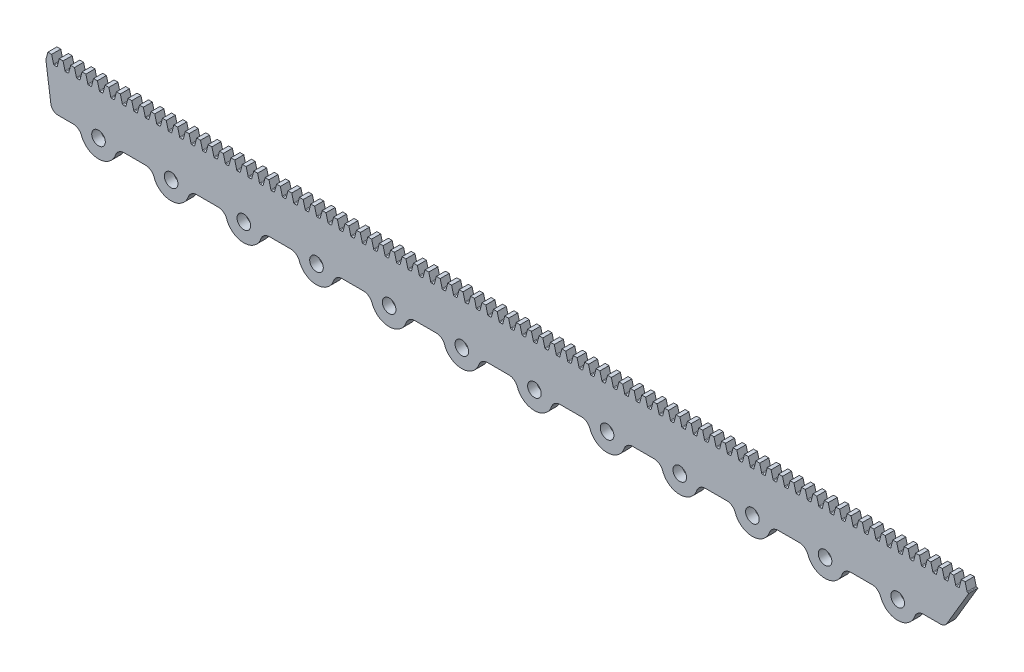
SolidWorks part; units mm, degrees
ref_plane "Front Plane" through (0, 0, 0) normal (0, 0, 1) x (1, 0, 0)
ref_plane "Top Plane" through (0, 0, 0) normal (0, 1, 0) x (1, 0, 0)
ref_plane "Right Plane" through (0, 0, 0) normal (1, 0, 0) x (0, 0, -1)
sketch "Sketch1" plane through (0, 0, 0) normal (0, 0, 1) x (1, 0, 0)
  line L0 (-103.4924, -0.9774) -> (-95.7557, 12.0777)
  line L4 (-379.696, 12.2681) -> (-380.3824, 14.9225)
  line L5 (-380.3824, 14.9225) -> (-381.7205, 14.9225)
  line L6 (-381.7205, 14.9225) -> (-382.4069, 12.2681)
  line L7 (-382.6528, 12.0777) -> (-383.4632, 12.0777)
  line L8 (-383.7092, 12.2681) -> (-384.3956, 14.9225)
  line L9 (-384.3956, 14.9225) -> (-385.7337, 14.9225)
  line L11 (-385.7337, 14.9225) -> (-386.4201, 12.2681)
  line L12 (-386.666, 12.0777) -> (-387.4764, 12.0777)
  line L13 (-387.7224, 12.2681) -> (-388.4088, 14.9225)
  line L14 (-388.4088, 14.9225) -> (-389.7469, 14.9225)
  line L15 (-389.7469, 14.9225) -> (-390.4333, 12.2681)
  line L16 (-390.6792, 12.0777) -> (-391.4896, 12.0777)
  line L17 (-391.7356, 12.2681) -> (-392.422, 14.9225)
  line L18 (-392.422, 14.9225) -> (-393.7601, 14.9225)
  line L19 (-393.7601, 14.9225) -> (-394.4465, 12.2681)
  line L20 (-394.6924, 12.0777) -> (-395.5028, 12.0777)
  line L21 (-395.7488, 12.2681) -> (-396.4352, 14.9225)
  line L22 (-396.4352, 14.9225) -> (-397.7733, 14.9225)
  line L23 (-397.7733, 14.9225) -> (-398.4597, 12.2681)
  line L24 (-398.7056, 12.0777) -> (-399.516, 12.0777)
  line L25 (-399.762, 12.2681) -> (-400.4484, 14.9225)
  line L26 (-400.4484, 14.9225) -> (-401.7865, 14.9225)
  line L27 (-401.7865, 14.9225) -> (-402.4729, 12.2681)
  line L28 (-402.7188, 12.0777) -> (-403.5292, 12.0777)
  line L29 (-403.7752, 12.2681) -> (-404.4616, 14.9225)
  line L30 (-404.4616, 14.9225) -> (-405.7997, 14.9225)
  line L31 (-405.7997, 14.9225) -> (-406.4861, 12.2681)
  line L32 (-406.732, 12.0777) -> (-407.5103, 12.0777)
  line L34 (-407.765, 12.2681) -> (-408.4515, 14.9225)
  line L35 (-408.4515, 14.9225) -> (-409.7895, 14.9225)
  line L36 (-409.7895, 14.9225) -> (-410.4759, 12.2681)
  line L37 (-411.5089, 12.0777) -> (-410.7219, 12.0777)
  line L38 (-415.7446, 12.2681) -> (-416.4311, 14.9225)
  line L39 (-416.4311, 14.9225) -> (-417.7691, 14.9225)
  line L40 (-417.7691, 14.9225) -> (-418.3293, 12.7565)
  line L41 (-391.0698, -2.2225) -> (-383.6303, -2.2225)
  line L42 (-411.7548, 12.2681) -> (-412.4413, 14.9225)
  line L43 (-412.4413, 14.9225) -> (-413.7793, 14.9225)
  line L44 (-413.7793, 14.9225) -> (-414.4658, 12.2681)
  line L48 (-414.1934, -2.4033) -> (-408.9633, -2.4033)
  line L49 (-418.3857, 11.7685) -> (-416.7089, -0.2153)
  line L50 (-415.4987, 12.0777) -> (-414.7117, 12.0777)
  line L1890 (-365.6698, -2.2225) -> (-358.2303, -2.2225)
  line L1891 (-340.2698, -2.2225) -> (-332.8303, -2.2225)
  line L1892 (-314.8698, -2.2225) -> (-307.4303, -2.2225)
  line L1893 (-289.4698, -2.2225) -> (-282.0303, -2.2225)
  line L1894 (-264.0698, -2.2225) -> (-256.6303, -2.2225)
  line L1895 (-238.6698, -2.2225) -> (-231.2303, -2.2225)
  line L1896 (-213.2698, -2.2225) -> (-205.8303, -2.2225)
  line L1897 (-187.8698, -2.2225) -> (-180.4303, -2.2225)
  line L1898 (-162.4698, -2.2225) -> (-155.0303, -2.2225)
  line L1899 (-137.0698, -2.2225) -> (-129.6303, -2.2225)
  line L1900 (-111.6698, -2.2225) -> (-105.6776, -2.2225)
  line L2472 (-95.7557, 12.0777) -> (-96.1493, 12.0777)
  line L2473 (-96.3952, 12.2681) -> (-97.0816, 14.9225)
  line L2474 (-97.0816, 14.9225) -> (-98.4197, 14.9225)
  line L2475 (-98.4197, 14.9225) -> (-99.1061, 12.2681)
  line L2476 (-99.352, 12.0777) -> (-100.1391, 12.0777)
  line L2477 (-100.385, 12.2681) -> (-101.0715, 14.9225)
  line L2478 (-101.0715, 14.9225) -> (-102.4095, 14.9225)
  line L2479 (-102.4095, 14.9225) -> (-103.096, 12.2681)
  line L2480 (-103.3419, 12.0777) -> (-104.1289, 12.0777)
  line L2481 (-104.3748, 12.2681) -> (-105.0613, 14.9225)
  line L2482 (-105.0613, 14.9225) -> (-106.3993, 14.9225)
  line L2483 (-106.3993, 14.9225) -> (-107.0858, 12.2681)
  line L2484 (-107.3317, 12.0777) -> (-108.1187, 12.0777)
  line L2485 (-108.3646, 12.2681) -> (-109.0511, 14.9225)
  line L2486 (-109.0511, 14.9225) -> (-110.3891, 14.9225)
  line L2487 (-110.3891, 14.9225) -> (-111.0756, 12.2681)
  line L2488 (-111.3215, 12.0777) -> (-112.1086, 12.0777)
  line L2489 (-112.3545, 12.2681) -> (-113.0409, 14.9225)
  line L2490 (-113.0409, 14.9225) -> (-114.379, 14.9225)
  line L2491 (-114.379, 14.9225) -> (-115.0654, 12.2681)
  line L2492 (-115.3113, 12.0777) -> (-116.0984, 12.0777)
  line L2493 (-116.3443, 12.2681) -> (-117.0308, 14.9225)
  line L2494 (-117.0308, 14.9225) -> (-118.3688, 14.9225)
  line L2495 (-118.3688, 14.9225) -> (-119.0553, 12.2681)
  line L2496 (-119.3012, 12.0777) -> (-120.0882, 12.0777)
  line L2497 (-120.3341, 12.2681) -> (-121.0206, 14.9225)
  line L2498 (-121.0206, 14.9225) -> (-122.3586, 14.9225)
  line L2499 (-122.3586, 14.9225) -> (-123.0451, 12.2681)
  line L2500 (-123.291, 12.0777) -> (-124.078, 12.0777)
  line L2501 (-124.3239, 12.2681) -> (-125.0104, 14.9225)
  line L2502 (-125.0104, 14.9225) -> (-126.3484, 14.9225)
  line L2503 (-126.3484, 14.9225) -> (-127.0349, 12.2681)
  line L2504 (-127.2808, 12.0777) -> (-128.0678, 12.0777)
  line L2505 (-128.3138, 12.2681) -> (-129.0002, 14.9225)
  line L2506 (-129.0002, 14.9225) -> (-130.3382, 14.9225)
  line L2507 (-130.3382, 14.9225) -> (-131.0247, 12.2681)
  line L2508 (-131.2706, 12.0777) -> (-132.0577, 12.0777)
  line L2509 (-132.3036, 12.2681) -> (-132.99, 14.9225)
  line L2510 (-132.99, 14.9225) -> (-134.3281, 14.9225)
  line L2511 (-134.3281, 14.9225) -> (-135.0145, 12.2681)
  line L2512 (-135.2605, 12.0777) -> (-136.0475, 12.0777)
  line L2513 (-136.2934, 12.2681) -> (-136.9799, 14.9225)
  line L2514 (-136.9799, 14.9225) -> (-138.3179, 14.9225)
  line L2515 (-138.3179, 14.9225) -> (-139.0044, 12.2681)
  line L2516 (-139.2503, 12.0777) -> (-140.0373, 12.0777)
  line L2517 (-140.2832, 12.2681) -> (-140.9697, 14.9225)
  line L2518 (-140.9697, 14.9225) -> (-142.3077, 14.9225)
  line L2519 (-142.3077, 14.9225) -> (-142.9942, 12.2681)
  line L2520 (-143.2401, 12.0777) -> (-144.0271, 12.0777)
  line L2521 (-144.273, 12.2681) -> (-144.9595, 14.9225)
  line L2522 (-144.9595, 14.9225) -> (-146.2975, 14.9225)
  line L2523 (-146.2975, 14.9225) -> (-146.984, 12.2681)
  line L2524 (-147.2299, 12.0777) -> (-148.017, 12.0777)
  line L2525 (-148.2629, 12.2681) -> (-148.9493, 14.9225)
  line L2526 (-148.9493, 14.9225) -> (-150.2874, 14.9225)
  line L2527 (-150.2874, 14.9225) -> (-150.9738, 12.2681)
  line L2528 (-151.2197, 12.0777) -> (-152.0068, 12.0777)
  line L2529 (-152.2527, 12.2681) -> (-152.9392, 14.9225)
  line L2530 (-152.9392, 14.9225) -> (-154.2772, 14.9225)
  line L2531 (-154.2772, 14.9225) -> (-154.9637, 12.2681)
  line L2532 (-155.2096, 12.0777) -> (-155.9966, 12.0777)
  line L2533 (-156.2425, 12.2681) -> (-156.929, 14.9225)
  line L2534 (-156.929, 14.9225) -> (-158.267, 14.9225)
  line L2535 (-158.267, 14.9225) -> (-158.9535, 12.2681)
  line L2536 (-159.1994, 12.0777) -> (-159.9864, 12.0777)
  line L2537 (-160.2323, 12.2681) -> (-160.9188, 14.9225)
  line L2538 (-160.9188, 14.9225) -> (-162.2568, 14.9225)
  line L2539 (-162.2568, 14.9225) -> (-162.9433, 12.2681)
  line L2540 (-163.1892, 12.0777) -> (-163.9762, 12.0777)
  line L2541 (-164.2222, 12.2681) -> (-164.9086, 14.9225)
  line L2542 (-164.9086, 14.9225) -> (-166.2467, 14.9225)
  line L2543 (-166.2467, 14.9225) -> (-166.9331, 12.2681)
  line L2544 (-167.179, 12.0777) -> (-167.9661, 12.0777)
  line L2545 (-168.212, 12.2681) -> (-168.8985, 14.9225)
  line L2546 (-168.8985, 14.9225) -> (-170.2365, 14.9225)
  line L2547 (-170.2365, 14.9225) -> (-170.9229, 12.2681)
  line L2548 (-171.1689, 12.0777) -> (-171.9559, 12.0777)
  line L2549 (-172.2018, 12.2681) -> (-172.8883, 14.9225)
  line L2550 (-172.8883, 14.9225) -> (-174.2263, 14.9225)
  line L2551 (-174.2263, 14.9225) -> (-174.9128, 12.2681)
  line L2552 (-175.1587, 12.0777) -> (-175.9457, 12.0777)
  line L2553 (-176.1916, 12.2681) -> (-176.8781, 14.9225)
  line L2554 (-176.8781, 14.9225) -> (-178.2161, 14.9225)
  line L2555 (-178.2161, 14.9225) -> (-178.9026, 12.2681)
  line L2556 (-179.1485, 12.0777) -> (-179.9355, 12.0777)
  line L2557 (-180.1814, 12.2681) -> (-180.8679, 14.9225)
  line L2558 (-180.8679, 14.9225) -> (-182.2059, 14.9225)
  line L2559 (-182.2059, 14.9225) -> (-182.8924, 12.2681)
  line L2560 (-183.1383, 12.0777) -> (-183.9254, 12.0777)
  line L2561 (-184.1713, 12.2681) -> (-184.8577, 14.9225)
  line L2562 (-184.8577, 14.9225) -> (-186.1958, 14.9225)
  line L2563 (-186.1958, 14.9225) -> (-186.8822, 12.2681)
  line L2564 (-187.1281, 12.0777) -> (-187.9152, 12.0777)
  line L2565 (-188.1611, 12.2681) -> (-188.8476, 14.9225)
  line L2566 (-188.8476, 14.9225) -> (-190.1856, 14.9225)
  line L2567 (-190.1856, 14.9225) -> (-190.8721, 12.2681)
  line L2568 (-191.118, 12.0777) -> (-191.905, 12.0777)
  line L2569 (-192.1509, 12.2681) -> (-192.8374, 14.9225)
  line L2570 (-192.8374, 14.9225) -> (-194.1754, 14.9225)
  line L2571 (-194.1754, 14.9225) -> (-194.8619, 12.2681)
  line L2572 (-195.1078, 12.0777) -> (-195.8948, 12.0777)
  line L2573 (-196.1407, 12.2681) -> (-196.8272, 14.9225)
  line L2574 (-196.8272, 14.9225) -> (-198.1652, 14.9225)
  line L2575 (-198.1652, 14.9225) -> (-198.8517, 12.2681)
  line L2576 (-199.0976, 12.0777) -> (-199.8847, 12.0777)
  line L2577 (-200.1306, 12.2681) -> (-200.817, 14.9225)
  line L2578 (-200.817, 14.9225) -> (-202.1551, 14.9225)
  line L2579 (-202.1551, 14.9225) -> (-202.8415, 12.2681)
  line L2580 (-203.0874, 12.0777) -> (-203.8745, 12.0777)
  line L2581 (-204.1204, 12.2681) -> (-204.8069, 14.9225)
  line L2582 (-204.8069, 14.9225) -> (-206.1449, 14.9225)
  line L2583 (-206.1449, 14.9225) -> (-206.8314, 12.2681)
  line L2584 (-207.0773, 12.0777) -> (-207.8643, 12.0777)
  line L2585 (-208.1102, 12.2681) -> (-208.7967, 14.9225)
  line L2586 (-208.7967, 14.9225) -> (-210.1347, 14.9225)
  line L2587 (-210.1347, 14.9225) -> (-210.8212, 12.2681)
  line L2588 (-211.0671, 12.0777) -> (-211.8541, 12.0777)
  line L2589 (-212.1, 12.2681) -> (-212.7865, 14.9225)
  line L2590 (-212.7865, 14.9225) -> (-214.1245, 14.9225)
  line L2591 (-214.1245, 14.9225) -> (-214.811, 12.2681)
  line L2592 (-215.0569, 12.0777) -> (-215.8439, 12.0777)
  line L2593 (-216.0899, 12.2681) -> (-216.7763, 14.9225)
  line L2594 (-216.7763, 14.9225) -> (-218.1143, 14.9225)
  line L2595 (-218.1143, 14.9225) -> (-218.8008, 12.2681)
  line L2596 (-219.0467, 12.0777) -> (-219.8338, 12.0777)
  line L2597 (-220.0797, 12.2681) -> (-220.7661, 14.9225)
  line L2598 (-220.7661, 14.9225) -> (-222.1042, 14.9225)
  line L2599 (-222.1042, 14.9225) -> (-222.7906, 12.2681)
  line L2600 (-223.0366, 12.0777) -> (-223.8236, 12.0777)
  line L2601 (-224.0695, 12.2681) -> (-224.756, 14.9225)
  line L2602 (-224.756, 14.9225) -> (-226.094, 14.9225)
  line L2603 (-226.094, 14.9225) -> (-226.7805, 12.2681)
  line L2604 (-227.0264, 12.0777) -> (-227.8134, 12.0777)
  line L2605 (-228.0593, 12.2681) -> (-228.7458, 14.9225)
  line L2606 (-228.7458, 14.9225) -> (-230.0838, 14.9225)
  line L2607 (-230.0838, 14.9225) -> (-230.7703, 12.2681)
  line L2608 (-231.0162, 12.0777) -> (-231.8032, 12.0777)
  line L2609 (-232.0491, 12.2681) -> (-232.7356, 14.9225)
  line L2610 (-232.7356, 14.9225) -> (-234.0736, 14.9225)
  line L2611 (-234.0736, 14.9225) -> (-234.7601, 12.2681)
  line L2612 (-235.006, 12.0777) -> (-235.7931, 12.0777)
  line L2613 (-236.039, 12.2681) -> (-236.7254, 14.9225)
  line L2614 (-236.7254, 14.9225) -> (-238.0635, 14.9225)
  line L2615 (-238.0635, 14.9225) -> (-238.7499, 12.2681)
  line L2616 (-238.9958, 12.0777) -> (-239.7829, 12.0777)
  line L2617 (-240.0288, 12.2681) -> (-240.7153, 14.9225)
  line L2618 (-240.7153, 14.9225) -> (-242.0533, 14.9225)
  line L2619 (-242.0533, 14.9225) -> (-242.7398, 12.2681)
  line L2620 (-242.9857, 12.0777) -> (-243.7727, 12.0777)
  line L2621 (-244.0186, 12.2681) -> (-244.7051, 14.9225)
  line L2622 (-244.7051, 14.9225) -> (-246.0431, 14.9225)
  line L2623 (-246.0431, 14.9225) -> (-246.7296, 12.2681)
  line L2624 (-246.9755, 12.0777) -> (-247.7625, 12.0777)
  line L2625 (-248.0084, 12.2681) -> (-248.6949, 14.9225)
  line L2626 (-248.6949, 14.9225) -> (-250.0329, 14.9225)
  line L2627 (-250.0329, 14.9225) -> (-250.7194, 12.2681)
  line L2628 (-250.9653, 12.0777) -> (-251.7523, 12.0777)
  line L2629 (-251.9983, 12.2681) -> (-252.6847, 14.9225)
  line L2630 (-252.6847, 14.9225) -> (-254.0228, 14.9225)
  line L2631 (-254.0228, 14.9225) -> (-254.7092, 12.2681)
  line L2632 (-254.9551, 12.0777) -> (-255.7422, 12.0777)
  line L2633 (-255.9881, 12.2681) -> (-256.6746, 14.9225)
  line L2634 (-256.6746, 14.9225) -> (-258.0126, 14.9225)
  line L2635 (-258.0126, 14.9225) -> (-258.699, 12.2681)
  line L2636 (-258.945, 12.0777) -> (-259.732, 12.0777)
  line L2637 (-259.9779, 12.2681) -> (-260.6644, 14.9225)
  line L2638 (-260.6644, 14.9225) -> (-262.0024, 14.9225)
  line L2639 (-262.0024, 14.9225) -> (-262.6889, 12.2681)
  line L2640 (-262.9348, 12.0777) -> (-263.7218, 12.0777)
  line L2641 (-263.9677, 12.2681) -> (-264.6542, 14.9225)
  line L2642 (-264.6542, 14.9225) -> (-265.9922, 14.9225)
  line L2643 (-265.9922, 14.9225) -> (-266.6787, 12.2681)
  line L2644 (-266.9246, 12.0777) -> (-267.7116, 12.0777)
  line L2645 (-267.9575, 12.2681) -> (-268.644, 14.9225)
  line L2646 (-268.644, 14.9225) -> (-269.982, 14.9225)
  line L2647 (-269.982, 14.9225) -> (-270.6685, 12.2681)
  line L2648 (-270.9144, 12.0777) -> (-271.7015, 12.0777)
  line L2649 (-271.9474, 12.2681) -> (-272.6338, 14.9225)
  line L2650 (-272.6338, 14.9225) -> (-273.9719, 14.9225)
  line L2651 (-273.9719, 14.9225) -> (-274.6583, 12.2681)
  line L2652 (-274.9042, 12.0777) -> (-275.6913, 12.0777)
  line L2653 (-275.9372, 12.2681) -> (-276.6237, 14.9225)
  line L2654 (-276.6237, 14.9225) -> (-277.9617, 14.9225)
  line L2655 (-277.9617, 14.9225) -> (-278.6482, 12.2681)
  line L2656 (-278.8941, 12.0777) -> (-279.6811, 12.0777)
  line L2657 (-279.927, 12.2681) -> (-280.6135, 14.9225)
  line L2658 (-280.6135, 14.9225) -> (-281.9515, 14.9225)
  line L2659 (-281.9515, 14.9225) -> (-282.638, 12.2681)
  line L2660 (-282.8839, 12.0777) -> (-283.6709, 12.0777)
  line L2661 (-283.9168, 12.2681) -> (-284.6033, 14.9225)
  line L2662 (-284.6033, 14.9225) -> (-285.9413, 14.9225)
  line L2663 (-285.9413, 14.9225) -> (-286.6278, 12.2681)
  line L2664 (-286.8737, 12.0777) -> (-287.6607, 12.0777)
  line L2665 (-287.9067, 12.2681) -> (-288.5931, 14.9225)
  line L2666 (-288.5931, 14.9225) -> (-289.9312, 14.9225)
  line L2667 (-289.9312, 14.9225) -> (-290.6176, 12.2681)
  line L2668 (-290.8635, 12.0777) -> (-291.6506, 12.0777)
  line L2669 (-291.8965, 12.2681) -> (-292.583, 14.9225)
  line L2670 (-292.583, 14.9225) -> (-293.921, 14.9225)
  line L2671 (-293.921, 14.9225) -> (-294.6075, 12.2681)
  line L2672 (-294.8534, 12.0777) -> (-295.6404, 12.0777)
  line L2673 (-295.8863, 12.2681) -> (-296.5728, 14.9225)
  line L2674 (-296.5728, 14.9225) -> (-297.9108, 14.9225)
  line L2675 (-297.9108, 14.9225) -> (-298.5973, 12.2681)
  line L2676 (-298.8432, 12.0777) -> (-299.6302, 12.0777)
  line L2677 (-299.8761, 12.2681) -> (-300.5626, 14.9225)
  line L2678 (-300.5626, 14.9225) -> (-301.9006, 14.9225)
  line L2679 (-301.9006, 14.9225) -> (-302.5871, 12.2681)
  line L2680 (-302.833, 12.0777) -> (-303.62, 12.0777)
  line L2681 (-303.8659, 12.2681) -> (-304.5524, 14.9225)
  line L2682 (-304.5524, 14.9225) -> (-305.8904, 14.9225)
  line L2683 (-305.8904, 14.9225) -> (-306.5769, 12.2681)
  line L2684 (-306.8228, 12.0777) -> (-307.6099, 12.0777)
  line L2685 (-307.8558, 12.2681) -> (-308.5422, 14.9225)
  line L2686 (-308.5422, 14.9225) -> (-309.8803, 14.9225)
  line L2687 (-309.8803, 14.9225) -> (-310.5667, 12.2681)
  line L2688 (-310.8127, 12.0777) -> (-311.5997, 12.0777)
  line L2689 (-311.8456, 12.2681) -> (-312.5321, 14.9225)
  line L2690 (-312.5321, 14.9225) -> (-313.8701, 14.9225)
  line L2691 (-313.8701, 14.9225) -> (-314.5566, 12.2681)
  line L2692 (-314.8025, 12.0777) -> (-315.5895, 12.0777)
  line L2693 (-315.8354, 12.2681) -> (-316.5219, 14.9225)
  line L2694 (-316.5219, 14.9225) -> (-317.8599, 14.9225)
  line L2695 (-317.8599, 14.9225) -> (-318.5464, 12.2681)
  line L2696 (-318.7923, 12.0777) -> (-319.5793, 12.0777)
  line L2697 (-319.8252, 12.2681) -> (-320.5117, 14.9225)
  line L2698 (-320.5117, 14.9225) -> (-321.8497, 14.9225)
  line L2699 (-321.8497, 14.9225) -> (-322.5362, 12.2681)
  line L2700 (-322.7821, 12.0777) -> (-323.5692, 12.0777)
  line L2701 (-323.8151, 12.2681) -> (-324.5015, 14.9225)
  line L2702 (-324.5015, 14.9225) -> (-325.8396, 14.9225)
  line L2703 (-325.8396, 14.9225) -> (-326.526, 12.2681)
  line L2704 (-326.7719, 12.0777) -> (-327.559, 12.0777)
  line L2705 (-327.8049, 12.2681) -> (-328.4914, 14.9225)
  line L2706 (-328.4914, 14.9225) -> (-329.8294, 14.9225)
  line L2707 (-329.8294, 14.9225) -> (-330.5159, 12.2681)
  line L2708 (-330.7618, 12.0777) -> (-331.5488, 12.0777)
  line L2709 (-331.7947, 12.2681) -> (-332.4812, 14.9225)
  line L2710 (-332.4812, 14.9225) -> (-333.8192, 14.9225)
  line L2711 (-333.8192, 14.9225) -> (-334.5057, 12.2681)
  line L2712 (-334.7516, 12.0777) -> (-335.5386, 12.0777)
  line L2713 (-335.7845, 12.2681) -> (-336.471, 14.9225)
  line L2714 (-336.471, 14.9225) -> (-337.809, 14.9225)
  line L2715 (-337.809, 14.9225) -> (-338.4955, 12.2681)
  line L2716 (-338.7414, 12.0777) -> (-339.5284, 12.0777)
  line L2717 (-339.7744, 12.2681) -> (-340.4608, 14.9225)
  line L2718 (-340.4608, 14.9225) -> (-341.7988, 14.9225)
  line L2719 (-341.7988, 14.9225) -> (-342.4853, 12.2681)
  line L2720 (-342.7312, 12.0777) -> (-343.5183, 12.0777)
  line L2721 (-343.7642, 12.2681) -> (-344.4506, 14.9225)
  line L2722 (-344.4506, 14.9225) -> (-345.7887, 14.9225)
  line L2723 (-345.7887, 14.9225) -> (-346.4751, 12.2681)
  line L2724 (-346.7211, 12.0777) -> (-347.5081, 12.0777)
  line L2725 (-347.754, 12.2681) -> (-348.4405, 14.9225)
  line L2726 (-348.4405, 14.9225) -> (-349.7785, 14.9225)
  line L2727 (-349.7785, 14.9225) -> (-350.465, 12.2681)
  line L2728 (-350.7109, 12.0777) -> (-351.4979, 12.0777)
  line L2729 (-351.7438, 12.2681) -> (-352.4303, 14.9225)
  line L2730 (-352.4303, 14.9225) -> (-353.7683, 14.9225)
  line L2731 (-353.7683, 14.9225) -> (-354.4548, 12.2681)
  line L2732 (-354.7007, 12.0777) -> (-355.4877, 12.0777)
  line L2733 (-355.7336, 12.2681) -> (-356.4201, 14.9225)
  line L2734 (-356.4201, 14.9225) -> (-357.7581, 14.9225)
  line L2735 (-357.7581, 14.9225) -> (-358.4446, 12.2681)
  line L2736 (-358.6905, 12.0777) -> (-359.4776, 12.0777)
  line L2737 (-359.7235, 12.2681) -> (-360.4099, 14.9225)
  line L2738 (-360.4099, 14.9225) -> (-361.748, 14.9225)
  line L2739 (-361.748, 14.9225) -> (-362.4344, 12.2681)
  line L2740 (-362.6803, 12.0777) -> (-363.4674, 12.0777)
  line L2741 (-363.7133, 12.2681) -> (-364.3998, 14.9225)
  line L2742 (-364.3998, 14.9225) -> (-365.7378, 14.9225)
  line L2743 (-365.7378, 14.9225) -> (-366.4243, 12.2681)
  line L2744 (-366.6702, 12.0777) -> (-367.4572, 12.0777)
  line L2745 (-367.7031, 12.2681) -> (-368.3896, 14.9225)
  line L2746 (-368.3896, 14.9225) -> (-369.7276, 14.9225)
  line L2747 (-369.7276, 14.9225) -> (-370.4141, 12.2681)
  line L2748 (-370.66, 12.0777) -> (-371.447, 12.0777)
  line L2749 (-371.6929, 12.2681) -> (-372.3794, 14.9225)
  line L2750 (-372.3794, 14.9225) -> (-373.7174, 14.9225)
  line L2751 (-373.7174, 14.9225) -> (-374.4039, 12.2681)
  line L2752 (-374.6498, 12.0777) -> (-375.4368, 12.0777)
  line L2753 (-375.6828, 12.2681) -> (-376.3692, 14.9225)
  line L2754 (-376.3692, 14.9225) -> (-377.7073, 14.9225)
  line L2755 (-377.7073, 14.9225) -> (-378.3937, 12.2681)
  line L2756 (-378.6396, 12.0777) -> (-379.45, 12.0777)
  arc A0 (-105.6776, -2.2225) -> (-103.4924, -0.9774) centre (-105.6776, 0.3175) ccw
  circle A5 centre (-374.65, -2.2225) radius 2.3813
  circle A6 centre (-349.25, -2.2225) radius 2.3813
  circle A7 centre (-323.85, -2.2225) radius 2.3813
  circle A8 centre (-298.45, -2.2225) radius 2.3813
  circle A9 centre (-273.05, -2.2225) radius 2.3813
  circle A10 centre (-247.65, -2.2225) radius 2.3813
  circle A11 centre (-222.25, -2.2225) radius 2.3813
  circle A12 centre (-196.85, -2.2225) radius 2.3813
  circle A13 centre (-171.45, -2.2225) radius 2.3813
  circle A14 centre (-146.05, -2.2225) radius 2.3813
  circle A15 centre (-120.65, -2.2225) radius 2.3813
  arc A17 (-382.6528, 12.0777) -> (-382.4069, 12.2681) centre (-382.6528, 12.3317) ccw
  arc A18 (-379.696, 12.2681) -> (-379.45, 12.0777) centre (-379.45, 12.3317) ccw
  arc A19 (-405.9698, -4.52) -> (-394.0632, -4.3392) centre (-400.05, -2.2225) ccw
  arc A20 (-386.666, 12.0777) -> (-386.4201, 12.2681) centre (-386.666, 12.3317) ccw
  arc A21 (-383.7092, 12.2681) -> (-383.4632, 12.0777) centre (-383.4632, 12.3317) ccw
  arc A22 (-390.6792, 12.0777) -> (-390.4333, 12.2681) centre (-390.6792, 12.3317) ccw
  arc A23 (-387.7224, 12.2681) -> (-387.4764, 12.0777) centre (-387.4764, 12.3317) ccw
  arc A24 (-394.6924, 12.0777) -> (-394.4465, 12.2681) centre (-394.6924, 12.3317) ccw
  arc A25 (-391.7356, 12.2681) -> (-391.4896, 12.0777) centre (-391.4896, 12.3317) ccw
  arc A26 (-398.7056, 12.0777) -> (-398.4597, 12.2681) centre (-398.7056, 12.3317) ccw
  circle A27 centre (-400.05, -2.2225) radius 2.3813
  arc A28 (-395.7488, 12.2681) -> (-395.5028, 12.0777) centre (-395.5028, 12.3317) ccw
  arc A29 (-402.7188, 12.0777) -> (-402.4729, 12.2681) centre (-402.7188, 12.3317) ccw
  arc A31 (-399.762, 12.2681) -> (-399.516, 12.0777) centre (-399.516, 12.3317) ccw
  arc A33 (-406.732, 12.0777) -> (-406.4861, 12.2681) centre (-406.732, 12.3317) ccw
  arc A34 (-403.7752, 12.2681) -> (-403.5292, 12.0777) centre (-403.5292, 12.3317) ccw
  arc A35 (-410.7219, 12.0777) -> (-410.4759, 12.2681) centre (-410.7219, 12.3317) ccw
  arc A36 (-407.765, 12.2681) -> (-407.5103, 12.0777) centre (-407.5189, 12.3317) ccw
  arc A37 (-394.0632, -4.3392) -> (-391.0698, -2.2225) centre (-391.0698, -5.3975) cw
  arc A38 (-415.7446, 12.2681) -> (-415.4987, 12.0777) centre (-415.4987, 12.3317) ccw
  arc A39 (-414.7117, 12.0777) -> (-414.4658, 12.2681) centre (-414.7117, 12.3317) ccw
  arc A40 (-411.7548, 12.2681) -> (-411.5089, 12.0777) centre (-411.5089, 12.3317) ccw
  arc A41 (-408.9633, -2.4033) -> (-405.9698, -4.52) centre (-408.9633, -5.5783) cw
  arc A43 (-383.6303, -2.2225) -> (-380.6369, -4.3392) centre (-383.6303, -5.3975) cw
  arc A44 (-416.7089, -0.2153) -> (-414.1934, -2.4033) centre (-414.1934, 0.1367) ccw
  arc A45 (-418.3293, 12.7565) -> (-418.3857, 11.7685) centre (-415.8702, 12.1205) ccw
  arc A1126 (-380.6369, -4.3392) -> (-368.6632, -4.3392) centre (-374.65, -2.2225) ccw
  arc A1127 (-365.6698, -2.2225) -> (-368.6632, -4.3392) centre (-365.6698, -5.3975) ccw
  arc A1128 (-355.2369, -4.3392) -> (-358.2303, -2.2225) centre (-358.2303, -5.3975) ccw
  arc A1129 (-355.2369, -4.3392) -> (-343.2632, -4.3392) centre (-349.25, -2.2225) ccw
  arc A1130 (-340.2698, -2.2225) -> (-343.2632, -4.3392) centre (-340.2698, -5.3975) ccw
  arc A1131 (-329.8369, -4.3392) -> (-332.8303, -2.2225) centre (-332.8303, -5.3975) ccw
  arc A1132 (-329.8369, -4.3392) -> (-317.8632, -4.3392) centre (-323.85, -2.2225) ccw
  arc A1133 (-314.8698, -2.2225) -> (-317.8632, -4.3392) centre (-314.8698, -5.3975) ccw
  arc A1134 (-304.4369, -4.3392) -> (-307.4303, -2.2225) centre (-307.4303, -5.3975) ccw
  arc A1135 (-304.4369, -4.3392) -> (-292.4632, -4.3392) centre (-298.45, -2.2225) ccw
  arc A1136 (-289.4698, -2.2225) -> (-292.4632, -4.3392) centre (-289.4698, -5.3975) ccw
  arc A1137 (-279.0369, -4.3392) -> (-282.0303, -2.2225) centre (-282.0303, -5.3975) ccw
  arc A1138 (-279.0369, -4.3392) -> (-267.0632, -4.3392) centre (-273.05, -2.2225) ccw
  arc A1139 (-264.0698, -2.2225) -> (-267.0632, -4.3392) centre (-264.0698, -5.3975) ccw
  arc A1140 (-253.6369, -4.3392) -> (-256.6303, -2.2225) centre (-256.6303, -5.3975) ccw
  arc A1141 (-253.6369, -4.3392) -> (-241.6632, -4.3392) centre (-247.65, -2.2225) ccw
  arc A1142 (-238.6698, -2.2225) -> (-241.6632, -4.3392) centre (-238.6698, -5.3975) ccw
  arc A1143 (-228.2369, -4.3392) -> (-231.2303, -2.2225) centre (-231.2303, -5.3975) ccw
  arc A1144 (-228.2369, -4.3392) -> (-216.2632, -4.3392) centre (-222.25, -2.2225) ccw
  arc A1145 (-213.2698, -2.2225) -> (-216.2632, -4.3392) centre (-213.2698, -5.3975) ccw
  arc A1146 (-202.8369, -4.3392) -> (-205.8303, -2.2225) centre (-205.8303, -5.3975) ccw
  arc A1147 (-202.8369, -4.3392) -> (-190.8632, -4.3392) centre (-196.85, -2.2225) ccw
  arc A1148 (-187.8698, -2.2225) -> (-190.8632, -4.3392) centre (-187.8698, -5.3975) ccw
  arc A1149 (-177.4369, -4.3392) -> (-180.4303, -2.2225) centre (-180.4303, -5.3975) ccw
  arc A1150 (-177.4369, -4.3392) -> (-165.4632, -4.3392) centre (-171.45, -2.2225) ccw
  arc A1151 (-162.4698, -2.2225) -> (-165.4632, -4.3392) centre (-162.4698, -5.3975) ccw
  arc A1152 (-152.0369, -4.3392) -> (-155.0303, -2.2225) centre (-155.0303, -5.3975) ccw
  arc A1153 (-152.0369, -4.3392) -> (-140.0632, -4.3392) centre (-146.05, -2.2225) ccw
  arc A1154 (-137.0698, -2.2225) -> (-140.0632, -4.3392) centre (-137.0698, -5.3975) ccw
  arc A1155 (-126.6369, -4.3392) -> (-129.6303, -2.2225) centre (-129.6303, -5.3975) ccw
  arc A1156 (-126.6369, -4.3392) -> (-114.6632, -4.3392) centre (-120.65, -2.2225) ccw
  arc A1157 (-111.6698, -2.2225) -> (-114.6632, -4.3392) centre (-111.6698, -5.3975) ccw
  arc A1499 (-96.3952, 12.2681) -> (-96.1493, 12.0777) centre (-96.1493, 12.3317) ccw
  arc A1500 (-99.352, 12.0777) -> (-99.1061, 12.2681) centre (-99.352, 12.3317) ccw
  arc A1501 (-100.385, 12.2681) -> (-100.1391, 12.0777) centre (-100.1391, 12.3317) ccw
  arc A1502 (-103.3419, 12.0777) -> (-103.096, 12.2681) centre (-103.3419, 12.3317) ccw
  arc A1503 (-104.3748, 12.2681) -> (-104.1289, 12.0777) centre (-104.1289, 12.3317) ccw
  arc A1504 (-107.3317, 12.0777) -> (-107.0858, 12.2681) centre (-107.3317, 12.3317) ccw
  arc A1505 (-108.3646, 12.2681) -> (-108.1187, 12.0777) centre (-108.1187, 12.3317) ccw
  arc A1506 (-111.3215, 12.0777) -> (-111.0756, 12.2681) centre (-111.3215, 12.3317) ccw
  arc A1507 (-112.3545, 12.2681) -> (-112.1086, 12.0777) centre (-112.1086, 12.3317) ccw
  arc A1508 (-115.3113, 12.0777) -> (-115.0654, 12.2681) centre (-115.3113, 12.3317) ccw
  arc A1509 (-116.3443, 12.2681) -> (-116.0984, 12.0777) centre (-116.0984, 12.3317) ccw
  arc A1510 (-119.3012, 12.0777) -> (-119.0553, 12.2681) centre (-119.3012, 12.3317) ccw
  arc A1511 (-120.3341, 12.2681) -> (-120.0882, 12.0777) centre (-120.0882, 12.3317) ccw
  arc A1512 (-123.291, 12.0777) -> (-123.0451, 12.2681) centre (-123.291, 12.3317) ccw
  arc A1513 (-124.3239, 12.2681) -> (-124.078, 12.0777) centre (-124.078, 12.3317) ccw
  arc A1514 (-127.2808, 12.0777) -> (-127.0349, 12.2681) centre (-127.2808, 12.3317) ccw
  arc A1515 (-128.3138, 12.2681) -> (-128.0678, 12.0777) centre (-128.0678, 12.3317) ccw
  arc A1516 (-131.2706, 12.0777) -> (-131.0247, 12.2681) centre (-131.2706, 12.3317) ccw
  arc A1517 (-132.3036, 12.2681) -> (-132.0577, 12.0777) centre (-132.0577, 12.3317) ccw
  arc A1518 (-135.2605, 12.0777) -> (-135.0145, 12.2681) centre (-135.2605, 12.3317) ccw
  arc A1519 (-136.2934, 12.2681) -> (-136.0475, 12.0777) centre (-136.0475, 12.3317) ccw
  arc A1520 (-139.2503, 12.0777) -> (-139.0044, 12.2681) centre (-139.2503, 12.3317) ccw
  arc A1521 (-140.2832, 12.2681) -> (-140.0373, 12.0777) centre (-140.0373, 12.3317) ccw
  arc A1522 (-143.2401, 12.0777) -> (-142.9942, 12.2681) centre (-143.2401, 12.3317) ccw
  arc A1523 (-144.273, 12.2681) -> (-144.0271, 12.0777) centre (-144.0271, 12.3317) ccw
  arc A1524 (-147.2299, 12.0777) -> (-146.984, 12.2681) centre (-147.2299, 12.3317) ccw
  arc A1525 (-148.2629, 12.2681) -> (-148.017, 12.0777) centre (-148.017, 12.3317) ccw
  arc A1526 (-151.2197, 12.0777) -> (-150.9738, 12.2681) centre (-151.2197, 12.3317) ccw
  arc A1527 (-152.2527, 12.2681) -> (-152.0068, 12.0777) centre (-152.0068, 12.3317) ccw
  arc A1528 (-155.2096, 12.0777) -> (-154.9637, 12.2681) centre (-155.2096, 12.3317) ccw
  arc A1529 (-156.2425, 12.2681) -> (-155.9966, 12.0777) centre (-155.9966, 12.3317) ccw
  arc A1530 (-159.1994, 12.0777) -> (-158.9535, 12.2681) centre (-159.1994, 12.3317) ccw
  arc A1531 (-160.2323, 12.2681) -> (-159.9864, 12.0777) centre (-159.9864, 12.3317) ccw
  arc A1532 (-163.1892, 12.0777) -> (-162.9433, 12.2681) centre (-163.1892, 12.3317) ccw
  arc A1533 (-164.2222, 12.2681) -> (-163.9762, 12.0777) centre (-163.9762, 12.3317) ccw
  arc A1534 (-167.179, 12.0777) -> (-166.9331, 12.2681) centre (-167.179, 12.3317) ccw
  arc A1535 (-168.212, 12.2681) -> (-167.9661, 12.0777) centre (-167.9661, 12.3317) ccw
  arc A1536 (-171.1689, 12.0777) -> (-170.9229, 12.2681) centre (-171.1689, 12.3317) ccw
  arc A1537 (-172.2018, 12.2681) -> (-171.9559, 12.0777) centre (-171.9559, 12.3317) ccw
  arc A1538 (-175.1587, 12.0777) -> (-174.9128, 12.2681) centre (-175.1587, 12.3317) ccw
  arc A1539 (-176.1916, 12.2681) -> (-175.9457, 12.0777) centre (-175.9457, 12.3317) ccw
  arc A1540 (-179.1485, 12.0777) -> (-178.9026, 12.2681) centre (-179.1485, 12.3317) ccw
  arc A1541 (-180.1814, 12.2681) -> (-179.9355, 12.0777) centre (-179.9355, 12.3317) ccw
  arc A1542 (-183.1383, 12.0777) -> (-182.8924, 12.2681) centre (-183.1383, 12.3317) ccw
  arc A1543 (-184.1713, 12.2681) -> (-183.9254, 12.0777) centre (-183.9254, 12.3317) ccw
  arc A1544 (-187.1281, 12.0777) -> (-186.8822, 12.2681) centre (-187.1281, 12.3317) ccw
  arc A1545 (-188.1611, 12.2681) -> (-187.9152, 12.0777) centre (-187.9152, 12.3317) ccw
  arc A1546 (-191.118, 12.0777) -> (-190.8721, 12.2681) centre (-191.118, 12.3317) ccw
  arc A1547 (-192.1509, 12.2681) -> (-191.905, 12.0777) centre (-191.905, 12.3317) ccw
  arc A1548 (-195.1078, 12.0777) -> (-194.8619, 12.2681) centre (-195.1078, 12.3317) ccw
  arc A1549 (-196.1407, 12.2681) -> (-195.8948, 12.0777) centre (-195.8948, 12.3317) ccw
  arc A1550 (-199.0976, 12.0777) -> (-198.8517, 12.2681) centre (-199.0976, 12.3317) ccw
  arc A1551 (-200.1306, 12.2681) -> (-199.8847, 12.0777) centre (-199.8847, 12.3317) ccw
  arc A1552 (-203.0874, 12.0777) -> (-202.8415, 12.2681) centre (-203.0874, 12.3317) ccw
  arc A1553 (-204.1204, 12.2681) -> (-203.8745, 12.0777) centre (-203.8745, 12.3317) ccw
  arc A1554 (-207.0773, 12.0777) -> (-206.8314, 12.2681) centre (-207.0773, 12.3317) ccw
  arc A1555 (-208.1102, 12.2681) -> (-207.8643, 12.0777) centre (-207.8643, 12.3317) ccw
  arc A1556 (-211.0671, 12.0777) -> (-210.8212, 12.2681) centre (-211.0671, 12.3317) ccw
  arc A1557 (-212.1, 12.2681) -> (-211.8541, 12.0777) centre (-211.8541, 12.3317) ccw
  arc A1558 (-215.0569, 12.0777) -> (-214.811, 12.2681) centre (-215.0569, 12.3317) ccw
  arc A1559 (-216.0899, 12.2681) -> (-215.8439, 12.0777) centre (-215.8439, 12.3317) ccw
  arc A1560 (-219.0467, 12.0777) -> (-218.8008, 12.2681) centre (-219.0467, 12.3317) ccw
  arc A1561 (-220.0797, 12.2681) -> (-219.8338, 12.0777) centre (-219.8338, 12.3317) ccw
  arc A1562 (-223.0366, 12.0777) -> (-222.7906, 12.2681) centre (-223.0366, 12.3317) ccw
  arc A1563 (-224.0695, 12.2681) -> (-223.8236, 12.0777) centre (-223.8236, 12.3317) ccw
  arc A1564 (-227.0264, 12.0777) -> (-226.7805, 12.2681) centre (-227.0264, 12.3317) ccw
  arc A1565 (-228.0593, 12.2681) -> (-227.8134, 12.0777) centre (-227.8134, 12.3317) ccw
  arc A1566 (-231.0162, 12.0777) -> (-230.7703, 12.2681) centre (-231.0162, 12.3317) ccw
  arc A1567 (-232.0491, 12.2681) -> (-231.8032, 12.0777) centre (-231.8032, 12.3317) ccw
  arc A1568 (-235.006, 12.0777) -> (-234.7601, 12.2681) centre (-235.006, 12.3317) ccw
  arc A1569 (-236.039, 12.2681) -> (-235.7931, 12.0777) centre (-235.7931, 12.3317) ccw
  arc A1570 (-238.9958, 12.0777) -> (-238.7499, 12.2681) centre (-238.9958, 12.3317) ccw
  arc A1571 (-240.0288, 12.2681) -> (-239.7829, 12.0777) centre (-239.7829, 12.3317) ccw
  arc A1572 (-242.9857, 12.0777) -> (-242.7398, 12.2681) centre (-242.9857, 12.3317) ccw
  arc A1573 (-244.0186, 12.2681) -> (-243.7727, 12.0777) centre (-243.7727, 12.3317) ccw
  arc A1574 (-246.9755, 12.0777) -> (-246.7296, 12.2681) centre (-246.9755, 12.3317) ccw
  arc A1575 (-248.0084, 12.2681) -> (-247.7625, 12.0777) centre (-247.7625, 12.3317) ccw
  arc A1576 (-250.9653, 12.0777) -> (-250.7194, 12.2681) centre (-250.9653, 12.3317) ccw
  arc A1577 (-251.9983, 12.2681) -> (-251.7523, 12.0777) centre (-251.7523, 12.3317) ccw
  arc A1578 (-254.9551, 12.0777) -> (-254.7092, 12.2681) centre (-254.9551, 12.3317) ccw
  arc A1579 (-255.9881, 12.2681) -> (-255.7422, 12.0777) centre (-255.7422, 12.3317) ccw
  arc A1580 (-258.945, 12.0777) -> (-258.699, 12.2681) centre (-258.945, 12.3317) ccw
  arc A1581 (-259.9779, 12.2681) -> (-259.732, 12.0777) centre (-259.732, 12.3317) ccw
  arc A1582 (-262.9348, 12.0777) -> (-262.6889, 12.2681) centre (-262.9348, 12.3317) ccw
  arc A1583 (-263.9677, 12.2681) -> (-263.7218, 12.0777) centre (-263.7218, 12.3317) ccw
  arc A1584 (-266.9246, 12.0777) -> (-266.6787, 12.2681) centre (-266.9246, 12.3317) ccw
  arc A1585 (-267.9575, 12.2681) -> (-267.7116, 12.0777) centre (-267.7116, 12.3317) ccw
  arc A1586 (-270.9144, 12.0777) -> (-270.6685, 12.2681) centre (-270.9144, 12.3317) ccw
  arc A1587 (-271.9474, 12.2681) -> (-271.7015, 12.0777) centre (-271.7015, 12.3317) ccw
  arc A1588 (-274.9042, 12.0777) -> (-274.6583, 12.2681) centre (-274.9042, 12.3317) ccw
  arc A1589 (-275.9372, 12.2681) -> (-275.6913, 12.0777) centre (-275.6913, 12.3317) ccw
  arc A1590 (-278.8941, 12.0777) -> (-278.6482, 12.2681) centre (-278.8941, 12.3317) ccw
  arc A1591 (-279.927, 12.2681) -> (-279.6811, 12.0777) centre (-279.6811, 12.3317) ccw
  arc A1592 (-282.8839, 12.0777) -> (-282.638, 12.2681) centre (-282.8839, 12.3317) ccw
  arc A1593 (-283.9168, 12.2681) -> (-283.6709, 12.0777) centre (-283.6709, 12.3317) ccw
  arc A1594 (-286.8737, 12.0777) -> (-286.6278, 12.2681) centre (-286.8737, 12.3317) ccw
  arc A1595 (-287.9067, 12.2681) -> (-287.6607, 12.0777) centre (-287.6607, 12.3317) ccw
  arc A1596 (-290.8635, 12.0777) -> (-290.6176, 12.2681) centre (-290.8635, 12.3317) ccw
  arc A1597 (-291.8965, 12.2681) -> (-291.6506, 12.0777) centre (-291.6506, 12.3317) ccw
  arc A1598 (-294.8534, 12.0777) -> (-294.6075, 12.2681) centre (-294.8534, 12.3317) ccw
  arc A1599 (-295.8863, 12.2681) -> (-295.6404, 12.0777) centre (-295.6404, 12.3317) ccw
  arc A1600 (-298.8432, 12.0777) -> (-298.5973, 12.2681) centre (-298.8432, 12.3317) ccw
  arc A1601 (-299.8761, 12.2681) -> (-299.6302, 12.0777) centre (-299.6302, 12.3317) ccw
  arc A1602 (-302.833, 12.0777) -> (-302.5871, 12.2681) centre (-302.833, 12.3317) ccw
  arc A1603 (-303.8659, 12.2681) -> (-303.62, 12.0777) centre (-303.62, 12.3317) ccw
  arc A1604 (-306.8228, 12.0777) -> (-306.5769, 12.2681) centre (-306.8228, 12.3317) ccw
  arc A1605 (-307.8558, 12.2681) -> (-307.6099, 12.0777) centre (-307.6099, 12.3317) ccw
  arc A1606 (-310.8127, 12.0777) -> (-310.5667, 12.2681) centre (-310.8127, 12.3317) ccw
  arc A1607 (-311.8456, 12.2681) -> (-311.5997, 12.0777) centre (-311.5997, 12.3317) ccw
  arc A1608 (-314.8025, 12.0777) -> (-314.5566, 12.2681) centre (-314.8025, 12.3317) ccw
  arc A1609 (-315.8354, 12.2681) -> (-315.5895, 12.0777) centre (-315.5895, 12.3317) ccw
  arc A1610 (-318.7923, 12.0777) -> (-318.5464, 12.2681) centre (-318.7923, 12.3317) ccw
  arc A1611 (-319.8252, 12.2681) -> (-319.5793, 12.0777) centre (-319.5793, 12.3317) ccw
  arc A1612 (-322.7821, 12.0777) -> (-322.5362, 12.2681) centre (-322.7821, 12.3317) ccw
  arc A1613 (-323.8151, 12.2681) -> (-323.5692, 12.0777) centre (-323.5692, 12.3317) ccw
  arc A1614 (-326.7719, 12.0777) -> (-326.526, 12.2681) centre (-326.7719, 12.3317) ccw
  arc A1615 (-327.8049, 12.2681) -> (-327.559, 12.0777) centre (-327.559, 12.3317) ccw
  arc A1616 (-330.7618, 12.0777) -> (-330.5159, 12.2681) centre (-330.7618, 12.3317) ccw
  arc A1617 (-331.7947, 12.2681) -> (-331.5488, 12.0777) centre (-331.5488, 12.3317) ccw
  arc A1618 (-334.7516, 12.0777) -> (-334.5057, 12.2681) centre (-334.7516, 12.3317) ccw
  arc A1619 (-335.7845, 12.2681) -> (-335.5386, 12.0777) centre (-335.5386, 12.3317) ccw
  arc A1620 (-338.7414, 12.0777) -> (-338.4955, 12.2681) centre (-338.7414, 12.3317) ccw
  arc A1621 (-339.7744, 12.2681) -> (-339.5284, 12.0777) centre (-339.5284, 12.3317) ccw
  arc A1622 (-342.7312, 12.0777) -> (-342.4853, 12.2681) centre (-342.7312, 12.3317) ccw
  arc A1623 (-343.7642, 12.2681) -> (-343.5183, 12.0777) centre (-343.5183, 12.3317) ccw
  arc A1624 (-346.7211, 12.0777) -> (-346.4751, 12.2681) centre (-346.7211, 12.3317) ccw
  arc A1625 (-347.754, 12.2681) -> (-347.5081, 12.0777) centre (-347.5081, 12.3317) ccw
  arc A1626 (-350.7109, 12.0777) -> (-350.465, 12.2681) centre (-350.7109, 12.3317) ccw
  arc A1627 (-351.7438, 12.2681) -> (-351.4979, 12.0777) centre (-351.4979, 12.3317) ccw
  arc A1628 (-354.7007, 12.0777) -> (-354.4548, 12.2681) centre (-354.7007, 12.3317) ccw
  arc A1629 (-355.7336, 12.2681) -> (-355.4877, 12.0777) centre (-355.4877, 12.3317) ccw
  arc A1630 (-358.6905, 12.0777) -> (-358.4446, 12.2681) centre (-358.6905, 12.3317) ccw
  arc A1631 (-359.7235, 12.2681) -> (-359.4776, 12.0777) centre (-359.4776, 12.3317) ccw
  arc A1632 (-362.6803, 12.0777) -> (-362.4344, 12.2681) centre (-362.6803, 12.3317) ccw
  arc A1633 (-363.7133, 12.2681) -> (-363.4674, 12.0777) centre (-363.4674, 12.3317) ccw
  arc A1634 (-366.6702, 12.0777) -> (-366.4243, 12.2681) centre (-366.6702, 12.3317) ccw
  arc A1635 (-367.7031, 12.2681) -> (-367.4572, 12.0777) centre (-367.4572, 12.3317) ccw
  arc A1636 (-370.66, 12.0777) -> (-370.4141, 12.2681) centre (-370.66, 12.3317) ccw
  arc A1637 (-371.6929, 12.2681) -> (-371.447, 12.0777) centre (-371.447, 12.3317) ccw
  arc A1638 (-374.6498, 12.0777) -> (-374.4039, 12.2681) centre (-374.6498, 12.3317) ccw
  arc A1639 (-375.6828, 12.2681) -> (-375.4368, 12.0777) centre (-375.4368, 12.3317) ccw
  arc A1640 (-378.6396, 12.0777) -> (-378.3937, 12.2681) centre (-378.6396, 12.3317) ccw
  dimension "D1" = 2.54
  dimension "D2" = 7
  dimension "D4" = 2.54
  dimension "D3" = 8
extrude "Boss-Extrude3" add sketch "Sketch1" along normal blind 3.175
